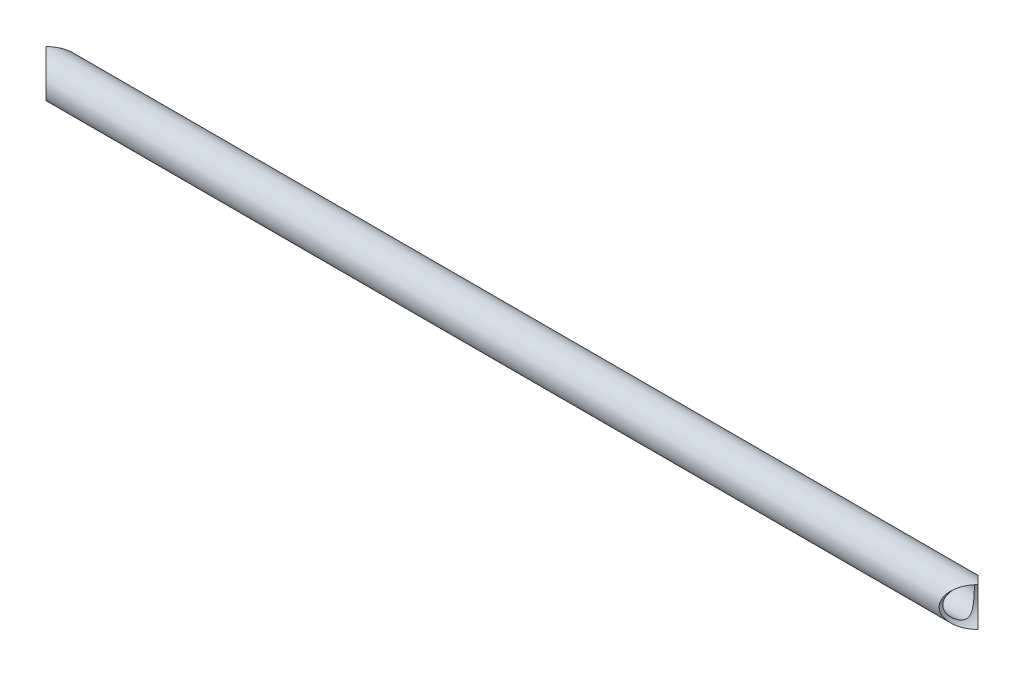
SolidWorks part; units mm, degrees
material "Aço inoxidável forjado"
ref_plane "Plano frontal" through (0, 0, 0) normal (0, 0, 1) x (1, 0, 0)
ref_plane "Plano superior" through (0, 0, 0) normal (0, 1, 0) x (1, 0, 0)
ref_plane "Plano direito" through (0, 0, 0) normal (1, 0, 0) x (0, 0, -1)
ref_plane "Plano1" through (0, 250, 0) normal (0, 1, 0) x (1, 0, 0)
sketch3d "3DSketch1"
  line L0 (803.885, 0, 257.4204) -> (803.885, 0, -257.4204) construction
  line L3 (803.885, 0, -257.4204) -> (0, 0, -200) construction
  line L4 (0, 0, -200) -> (0, 0, 200) construction
  line L5 (0, 0, 200) -> (803.885, 0, 257.4204) construction
sketch "Esboço3" plane through (0, 250, 0) normal (0, 1, 0) x (1, 0, 0)
  line L0 (0, 200) -> (0, -200) construction
  line L1 (0, -200) -> (803.885, -257.4204) construction
  line L2 (803.885, 257.4204) -> (803.885, -257.4204)
  line L3 (803.885, 257.4204) -> (0, 200) construction
sketch "Esboço8" plane through (0, 0, 0) normal (0, 1, 0) x (1, 0, 0)
  line L0 (0, 162.7552) -> (0, -162.7552) construction
  line L1 (0, 0) -> (910, 0) construction
  line L2 (910, 265) -> (910, -265) construction
  line L3 (37.1501, 202.6536) -> (910, 265) construction
  line L4 (37.1501, -202.6536) -> (910, -265) construction
  arc A0 (0, -162.7552) -> (37.1501, -202.6536) centre (40, -162.7552) ccw construction
  arc A1 (0, 162.7552) -> (37.1501, 202.6536) centre (40, 162.7552) cw construction
  point P9 (0, -200)
  point P12 (0, 200)
  dimension "D3" = 40
  dimension "D1" = 400
  dimension "D2" = 910
  dimension "D4" = 530
sketch "Esboço9" plane through (0, 250, 0) normal (0, 1, 0) x (1, 0, 0)
  line L0 (0, 162.7552) -> (0, -162.7552) construction
  line L1 (0, 0) -> (910, 0) construction
  line L2 (910, 265) -> (910, -265) construction
  line L3 (37.1501, 202.6536) -> (910, 265) construction
  line L4 (37.1501, -202.6536) -> (910, -265) construction
  arc A0 (0, -162.7552) -> (37.1501, -202.6536) centre (40, -162.7552) ccw construction
  arc A1 (0, 162.7552) -> (37.1501, 202.6536) centre (40, 162.7552) cw construction
  point P9 (0, -200)
  point P12 (0, 200)
  dimension "D3" = 40
  dimension "D1" = 400
  dimension "D2" = 910
  dimension "D4" = 530
ref_plane "Plano3" through (0, 910, 0) normal (0, 1, 0) x (1, 0, 0)
sketch "Esboço10" plane through (0, 910, 0) normal (0, 1, 0) x (1, 0, 0)
  line L0 (0, 162.4326) -> (0, -163.0779) construction
  line L1 (0, 0) -> (910, 0) construction
  line L2 (910, 265) -> (910, -265) construction
  line L3 (37.1354, 202.3299) -> (910, 265) construction
  line L4 (37.1648, -202.9773) -> (910, -265) construction
  arc A0 (0, -163.0779) -> (37.1648, -202.9773) centre (40, -163.0779) ccw construction
  arc A1 (0, 162.4326) -> (37.1354, 202.3299) centre (40, 162.4326) cw construction
  point P9 (0, -200.3364)
  point P12 (0, 199.6636)
  dimension "D3" = 40
  dimension "D1" = 400
  dimension "D2" = 910
sketch3d "3DSketch3"
  line L0 (910, 0, 265) -> (910, 139.2691, 265)
  line L1 (904.6546, 159.2691, 264.6182) -> (858.6942, 239.0777, 261.3353)
  line L2 (0, 250, 200) -> (803.885, 250, 257.4204) construction
  line L3 (853.5006, 262.564, 260.9643) -> (910, 910, 265)
  line L5 (37.1501, 250, 202.6536) -> (910, 250, 265) construction
  arc A0 (910, 139.2691, 265) -> (904.6546, 159.2691, 264.6182) centre (870.1017, 139.2691, 262.1501) ccw
  arc A1 (858.6942, 239.0777, 261.3353) -> (853.5006, 262.564, 260.9643) centre (893.2472, 259.0777, 263.8034) ccw
  point P10 (910, 149.987, 265)
  point P11 (867.2518, 139.2691, 302.0485)
  point P14 (852.4042, 250, 260.886)
  point P15 (896.097, 259.0777, 223.905)
  point P16 (854.3898, 250, 261.0278)
  dimension "D3" = 40
  dimension "D1" = 150
  dimension "D2" = 145
sketch "Esboço11" plane through (0, 0, 0) normal (0, 1, 0) x (1, 0, 0)
  circle A0 centre (910, -265) radius 7.9375
  dimension "D1" = 15.875
sketch3d "3DSketch4"
  line L0 (910, 0, -265) -> (910, 139.2691, -265)
  line L1 (904.6546, 159.2691, -264.6182) -> (858.6942, 239.0777, -261.3353)
  line L2 (803.885, 250, -257.4204) -> (0, 250, -200) construction
  line L3 (853.5006, 262.564, -260.9643) -> (910, 910, -265)
  line L4 (37.1501, 250, -202.6536) -> (910, 250, -265) construction
  arc A0 (858.6942, 239.0777, -261.3353) -> (853.5006, 262.564, -260.9643) centre (893.2472, 259.0777, -263.8034) ccw
  arc A1 (910, 139.2691, -265) -> (904.6546, 159.2691, -264.6182) centre (870.1017, 139.2691, -262.1501) ccw
  point P10 (852.4042, 250, -260.886)
  point P11 (890.3973, 259.0777, -303.7017)
  point P14 (910, 149.987, -265)
  point P15 (872.9515, 139.2691, -222.2518)
  point P16 (854.3898, 250, -261.0278)
  dimension "D3" = 40
  dimension "D1" = 150
  dimension "D2" = 145
sketch "Esboço12" plane through (0, 0, 0) normal (0, 1, 0) x (1, 0, 0)
  circle A0 centre (910, 265) radius 7.9375
  dimension "D1" = 15.875
sketch "Esboço13" plane through (0, 250, 0) normal (0, 1, 0) x (1, 0, 0)
  line L0 (0, 200) -> (0, -200) construction
  line L1 (0, -200) -> (854.3898, -261.0278) construction
  line L2 (854.3898, -261.0278) -> (854.3898, 261.0278) construction
  line L3 (854.3898, 261.0278) -> (0, 200) construction
  line L4 (854.3898, 261.0278) -> (854.3898, -261.0278)
  line L5 (0, 0) -> (910, 0) construction
  point P6 (854.3898, 150)
  point P7 (854.3898, -150)
  dimension "D1" = 150
  dimension "D2" = 150
sketch3d "3DSketch5"
  line L0 (473.5751, 0, 233.8268) -> (473.5751, 230, 233.8268)
  line L1 (37.1501, 0, 202.6536) -> (910, 0, 265) construction
  line L2 (0, 250, 200) -> (803.885, 250, 257.4204) construction
  line L3 (473.5751, 250, 213.8268) -> (473.5751, 250, -213.8268)
  line L4 (803.885, 250, -257.4204) -> (0, 250, -200) construction
  line L5 (473.5751, 230, -233.8268) -> (473.5751, 0, -233.8268)
  line L6 (803.885, 0, -257.4204) -> (0, 0, -200) construction
  arc A0 (473.5751, 250, -213.8268) -> (473.5751, 230, -233.8268) centre (473.5751, 230, -213.8268) ccw
  arc A1 (473.5751, 230, 233.8268) -> (473.5751, 250, 213.8268) centre (473.5751, 230, 213.8268) ccw
  point P16 (473.5751, 250, -233.8268)
  point P17 (453.5751, 230, -213.8268)
  point P18 (473.5751, 250, 233.8268)
  point P19 (453.5751, 230, 213.8268)
  dimension "D1" = 20
sketch "Esboço15" plane through (0, 250, 0) normal (0, 1, 0) x (1, 0, 0)
  line L0 (854.3898, -150) -> (473.5751, -150)
  line L3 (473.5751, -213.8268) -> (473.5751, 213.8268) construction
  line L4 (0, 0) -> (910, 0) construction
  dimension "D1" = 150
other "Pipe - configured 21.3 X 2.3(7)"
ref_plane "Plano4" through (854.3898, 250, 150) normal (-1, 0, 0) x (0, 0, 1)
sketch "Sketch1" plane through (854.3898, 250, 150) normal (-1, 0, 0) x (0, 0, 1)
  circle A0 centre (0, 0) radius 6.4375
  circle A1 centre (0, 0) radius 7.9375
  point P3 (0, 0)
  dimension "Out_dia" = 15.875
  dimension "D1" = 1.5
sketch "Esboço17" plane through (0, 0, 0) normal (0, 0, 1) x (1, 0, 0)
  line L0 (854.3898, 257.9375) -> (473.5751, 257.9375) construction
  circle A0 centre (473.5751, 250) radius 7.9375
  circle A1 centre (854.3898, 250) radius 7.9375
extrude "Corte-extrusão1" cut sketch "Esboço17" against normal through all both and the other way through all
